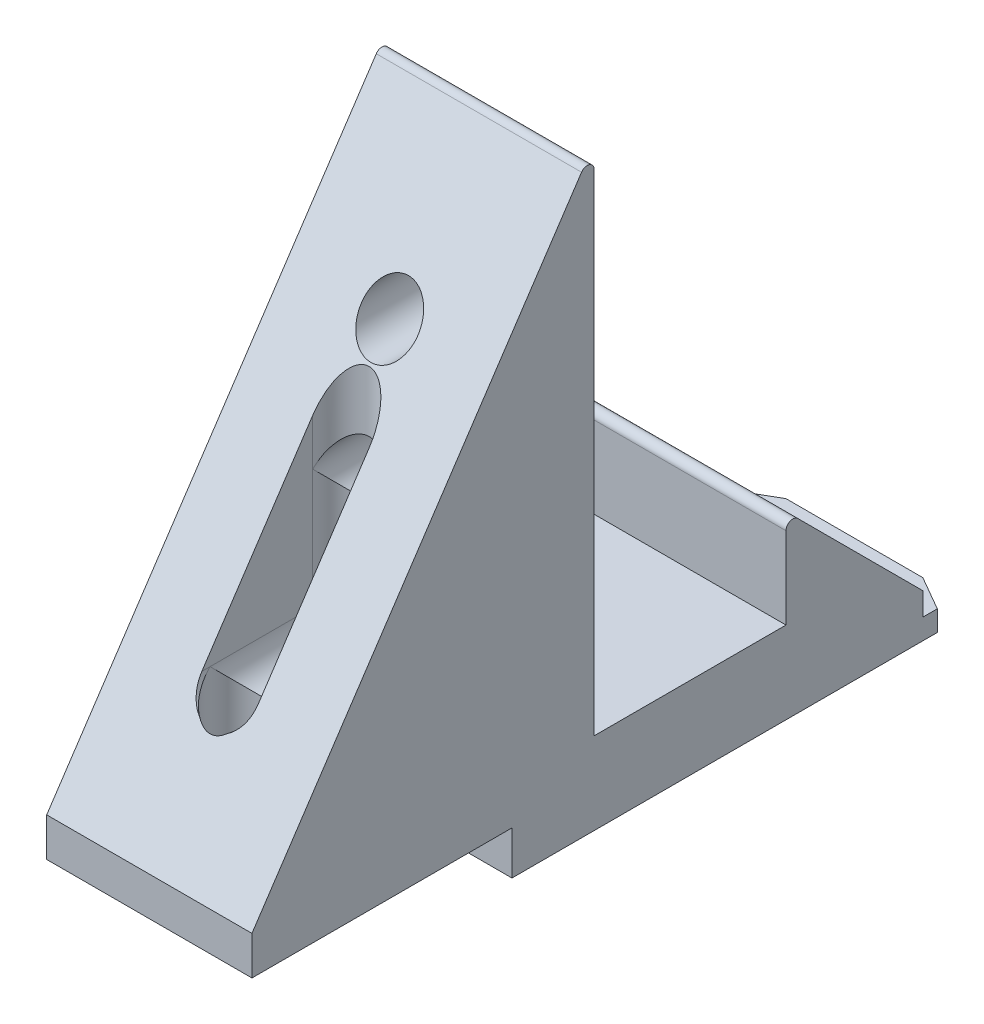
SolidWorks part; units mm, degrees
ref_plane "Front Plane" through (0, 0, 0) normal (0, 0, 1) x (1, 0, 0)
ref_plane "Top Plane" through (0, 0, 0) normal (0, 1, 0) x (1, 0, 0)
ref_plane "Right Plane" through (0, 0, 0) normal (1, 0, 0) x (0, 0, -1)
sketch "Sketch2" plane through (0, 0, 0) normal (1, 0, 0) x (0, 0, -1)
  line L0 (0, 5.65) -> (0, 80.65)
  line L2 (-50, 0) -> (0, 0) construction
  line L3 (-50, 0) -> (0, 0) construction
  line L4 (0, 0) -> (28.05, 0) construction
  line L5 (-50, 0) -> (-50, -6.35)
  line L6 (-50, -6.35) -> (48.05, -6.35)
  line L7 (48.05, 0) -> (48.05, -6.35)
  line L8 (28.05, 0) -> (48.05, 0) construction
  line L9 (48.05, 0) -> (28.05, 0) construction
  line L12 (28.05, 5.65) -> (28.05, 20)
  line L13 (48.05, 0) -> (28.05, 20)
  line L14 (0, 5.65) -> (28.05, 5.65)
  line L15 (0, 0) -> (0, 5.65) construction
  line L16 (28.05, 0) -> (28.05, 5.65) construction
  line L17 (-50, 0) -> (-50, 5.65)
  line L18 (-50, 5.65) -> (0, 80.65)
  dimension "D1" = 50
  dimension "D2" = 28.05
  dimension "D3" = 6.35
  dimension "D4" = 20
  dimension "D5" = 75
  dimension "D6" = 20
  dimension "D7" = 12
extrude "Boss-Extrude1" add sketch "Sketch2" along normal mid plane 30
fillet "Fillet1" radius 1 2 edges at (0, 20, -28.05) (0, 80.65, 0)
sketch "Sketch6" plane through (0, -6.35, 0) normal (0, -1, 0) x (1, 0, 0)
  line L0 (15, 50) -> (15, -48.05) construction
  line L1 (-15, 50) -> (15, 50)
  line L2 (-15, 50) -> (-15, 12)
  line L3 (-15, 12) -> (15, 12)
  line L4 (15, 50) -> (15, 12)
  dimension "D1" = 38
extrude "Cut-Extrude2" cut sketch "Sketch6" against normal blind 6.35
hole_wizard "M4 Clearance Hole1" positions "Sketch10" profile "Sketch8" hole size "M4" standard "ANSI Metric" end condition through all
sketch "Sketch10" plane through (0, 0, 0) normal (0, 0, -1) x (-1, 0, 0)
  line L0 (0, 78.3472) -> (0, 0) construction
  line L3 (15, 78.3472) -> (-15, 78.3472) construction
  point P0 (0, 58.3472)
  point P2 (0, 40.8472)
  point P4 (0, 23.3472)
  dimension "D1" = 20
  dimension "D2" = 17.5
  dimension "D3" = 17.5
sketch "Sketch8" plane through (0, 58.3472, 0) normal (1, 0, 0) x (0, 1, 0)
  line L0 (0, 0) -> (0, 50)
  line L1 (0, 50) -> (2.25, 50)
  line L2 (2.25, 50) -> (2.25, 0)
  line L5 (2.25, 0) -> (0, 0)
  line L11 (0, -6.35) -> (0, 107.95) construction
  dimension "Thru Hole Dia." = 4.5
  dimension "Thru Hole Depth" = 50
sketch "Sketch11" plane through (0, 0, 0) normal (0, 0, -1) x (-1, 0, 0)
  circle A0 centre (0, 58.3472) radius 4.125
  circle A1 centre (0, 40.8472) radius 4.125
  circle A2 centre (0, 23.3472) radius 4.125
  dimension "D1" = 8.25
extrude "Cut-Extrude3" cut sketch "Sketch11" against normal blind 40.35 from offset 5 offset against normal yes
hole_wizard "M4 Clearance Hole2" positions "Sketch17" profile "Sketch13" hole size "M4" standard "ANSI Metric" end condition through all
sketch "Sketch17" plane through (0, 0, 0) normal (0, -1, 0) x (-1, 0, 0)
  line L2 (0, -37) -> (0, -22) construction
  line L6 (15, -12) -> (-15, -12) construction
  point P0 (0, -37)
  point P4 (0, -22)
  dimension "D1" = 10
  dimension "D2" = 15
sketch "Sketch13" plane through (0, 0, 37) normal (1, 0, 0) x (0, 0, -1)
  line L0 (0, 0) -> (0, 78.3472)
  line L1 (0, 78.3472) -> (2.25, 78.3472)
  line L2 (2.25, 78.3472) -> (2.25, 0)
  line L5 (2.25, 0) -> (0, 0)
  line L11 (0, -6.35) -> (0, 107.95) construction
  dimension "Thru Hole Dia." = 4.5
  dimension "Thru Hole Depth" = 78.3472
sketch "Sketch15" plane through (0, 0, 0) normal (0, -1, 0) x (1, 0, 0)
  circle A0 centre (0, 37) radius 4.125
  circle A1 centre (0, 22) radius 4.125
  dimension "D1" = 8.25
extrude "Cut-Extrude4" cut sketch "Sketch15" against normal blind 78.35 from offset 4 offset against normal yes
ref_plane "Plane1" through (-4.125, 0, 0) normal (1, 0, 0) x (0, 0, -1)
sketch "Sketch16" plane through (-4.125, 0, 0) normal (1, 0, 0) x (0, 0, -1)
  line L0 (-22, 23.3472) -> (-17.875, 19.2222) construction
  line L1 (-22, 23.3472) -> (-17.875, 19.2222)
  line L3 (-22, 23.3472) -> (-44.0544, 23.3472)
  line L4 (-22, 23.3472) -> (-22, 52.6159)
  line L5 (-22, 52.6159) -> (-44.0544, 52.6159)
  line L6 (-44.0544, 23.3472) -> (-44.0544, 52.6159)
extrude "Cut-Extrude6" cut sketch "Sketch16" along normal up to vertex (8.25 mm away) contours L6 L3 L4 L5
sketch "Sketch18" plane through (0, -6.35, 0) normal (0, -1, 0) x (1, 0, 0)
  line L1 (-15, -48.05) -> (15, -48.05)
  line L2 (-15, -48.05) -> (-15, -53.05)
  line L3 (-15, -53.05) -> (15, -53.05)
  line L4 (15, -48.05) -> (15, -53.05)
  line L5 (15, 12) -> (15, -48.05) construction
  dimension "D1" = 5
extrude "Boss-Extrude2" add sketch "Sketch18" against normal blind 3
chamfer "Chamfer1" distance 5 angle 30 2 edges at (-15, -4.85, -53.05) (15, -4.85, -53.05)
